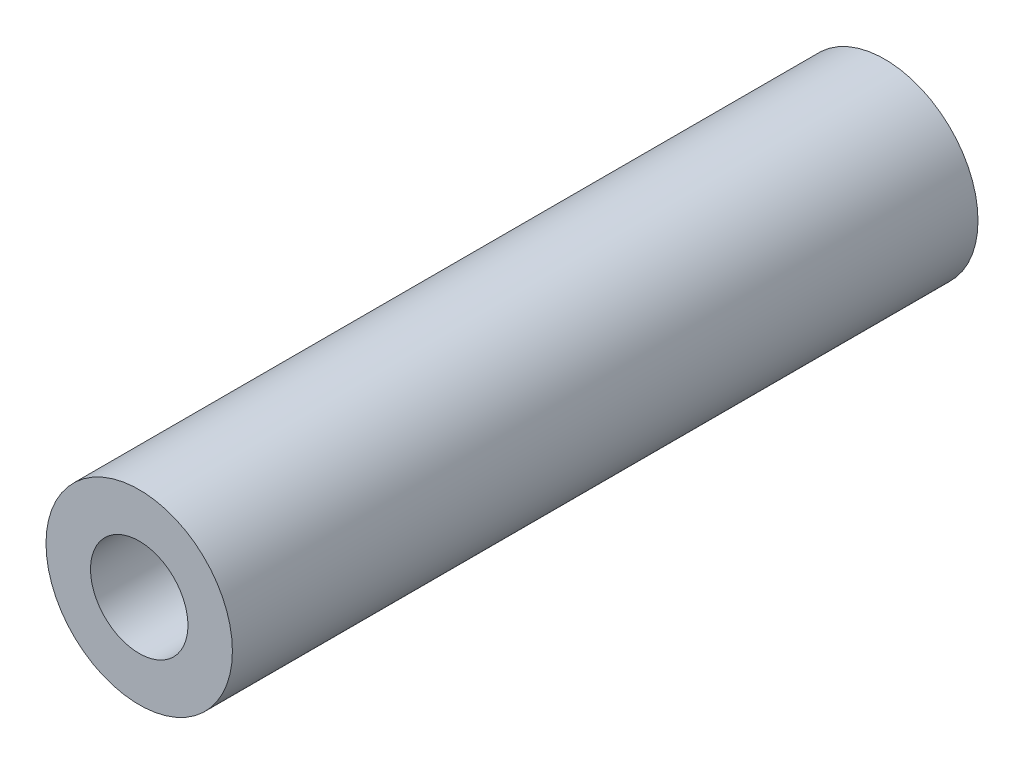
SolidWorks part; units mm, degrees
material "6061-T6 (SS)"
ref_plane "Front Plane" through (0, 0, 0) normal (0, 0, 1) x (1, 0, 0)
ref_plane "Top Plane" through (0, 0, 0) normal (0, 1, 0) x (1, 0, 0)
ref_plane "Right Plane" through (0, 0, 0) normal (1, 0, 0) x (0, 0, -1)
sketch "Sketch1" plane through (0, 0, 0) normal (0, 0, 1) x (1, 0, 0)
  circle A0 centre (0, 0) radius 2.4892
  circle A1 centre (0, 0) radius 4.7625
  dimension "D1" = 4.9784
  dimension "D2" = 9.525
extrude "Boss-Extrude1" add sketch "Sketch1" along normal blind 38.1
